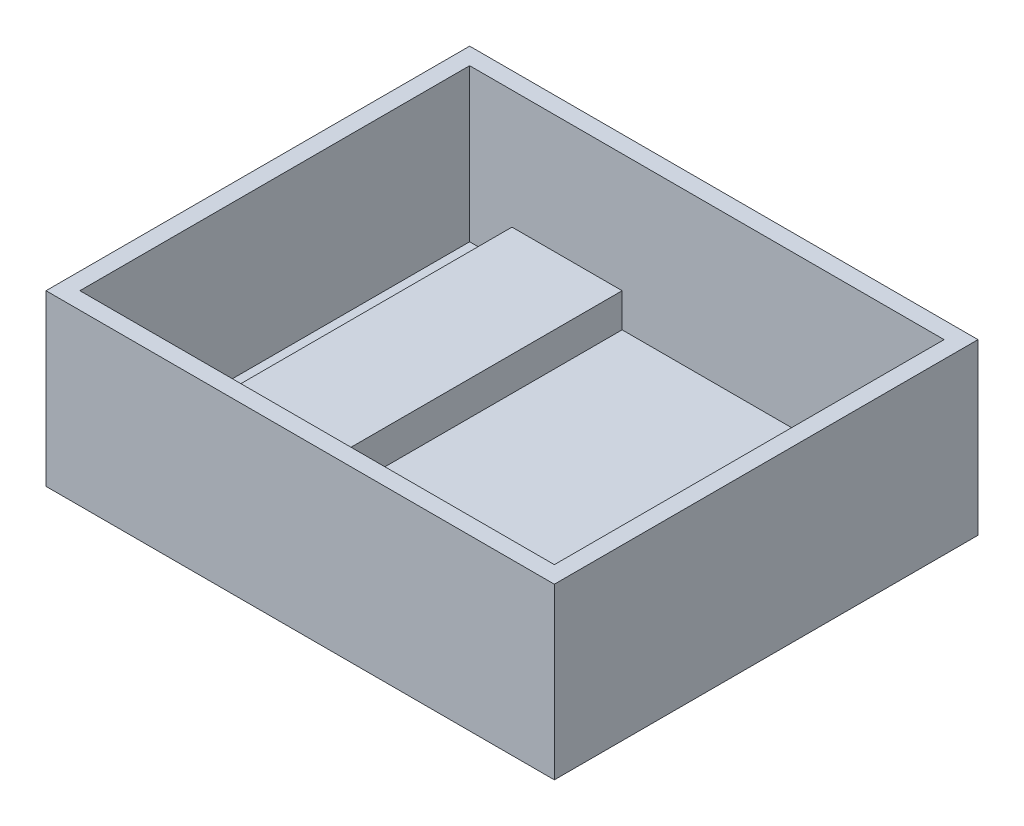
SolidWorks part; units mm, degrees
ref_plane "Front Plane" through (0, 0, 0) normal (0, 0, 1) x (1, 0, 0)
ref_plane "Top Plane" through (0, 0, 0) normal (0, 1, 0) x (1, 0, 0)
ref_plane "Right Plane" through (0, 0, 0) normal (1, 0, 0) x (0, 0, -1)
sketch "Sketch1" plane through (0, 0, 0) normal (0, 1, 0) x (1, 0, 0)
  line L1 (-70.5712, -39.9173) -> (49.4288, -39.9173)
  line L2 (-70.5712, -39.9173) -> (-70.5712, 60.0827)
  line L3 (-70.5712, 60.0827) -> (49.4288, 60.0827)
  line L4 (49.4288, -39.9173) -> (49.4288, 60.0827)
  dimension "D1" = 120
  dimension "D2" = 100
extrude "Boss-Extrude1" add sketch "Sketch1" along normal blind 40
sketch "Sketch2" plane through (0, 40, 0) normal (0, 1, 0) x (1, 0, 0)
  line L0 (49.4288, 60.0827) -> (-70.5712, 60.0827) construction
  line L1 (-66.5712, 56.0827) -> (45.4288, 56.0827)
  line L2 (-66.5712, 56.0827) -> (-66.5712, -35.9173)
  line L3 (-66.5712, -35.9173) -> (45.4288, -35.9173)
  line L4 (45.4288, 56.0827) -> (45.4288, -35.9173)
  line L5 (-70.5712, -39.9173) -> (49.4288, -39.9173) construction
  line L6 (-70.5712, 60.0827) -> (-70.5712, -39.9173) construction
  line L7 (49.4288, -39.9173) -> (49.4288, 60.0827) construction
  dimension "D1" = 4
  dimension "D2" = 4
  dimension "D3" = 4
  dimension "D4" = 4
extrude "Cut-Extrude1" cut sketch "Sketch2" against normal blind 36
sketch "Sketch3" plane through (0, 4, 0) normal (0, 1, 0) x (1, 0, 0)
  line L0 (-66.5712, 56.0827) -> (-66.5712, -35.9173) construction
  line L1 (49.4288, 60.0827) -> (-70.5712, 60.0827) construction
  line L2 (-56.5712, 60.0827) -> (-30.5712, 60.0827)
  line L3 (-56.5712, 60.0827) -> (-56.5712, -9.9173)
  line L4 (-56.5712, -9.9173) -> (-30.5712, -9.9173)
  line L5 (-30.5712, 60.0827) -> (-30.5712, -9.9173)
  dimension "D1" = 26
  dimension "D2" = 70
  dimension "D3" = 10
extrude "Boss-Extrude3" add sketch "Sketch3" along normal blind 8
